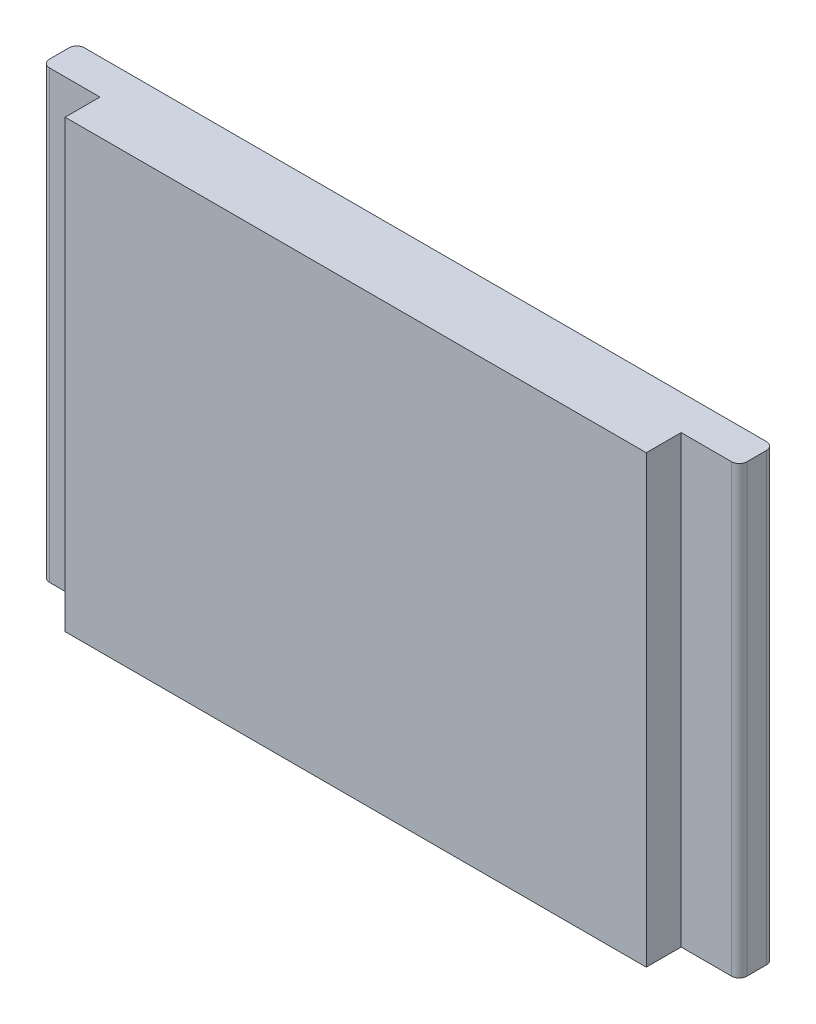
SolidWorks part; units mm, degrees
ref_plane "Front Plane" through (0, 0, 0) normal (0, 0, 1) x (1, 0, 0)
ref_plane "Top Plane" through (0, 0, 0) normal (0, 1, 0) x (1, 0, 0)
ref_plane "Right Plane" through (0, 0, 0) normal (1, 0, 0) x (0, 0, -1)
sketch "Sketch1" plane through (0, 0, 0) normal (0, 1, 0) x (1, 0, 0)
  line L8 (-98.7886, 34.8082) -> (-98.7886, 29.8082)
  line L9 (-96.7886, 27.8082) -> (-83.7886, 27.8082)
  line L10 (-83.7886, 27.8082) -> (-83.7886, 18.8082)
  line L11 (-83.7886, 18.8082) -> (66.2114, 18.8082)
  line L12 (66.2114, 18.8082) -> (66.2114, 27.8082)
  line L13 (66.2114, 27.8082) -> (79.2114, 27.8082)
  line L14 (81.2114, 29.8082) -> (81.2114, 34.8082)
  line L15 (79.2114, 36.8082) -> (-96.7886, 36.8082)
  arc A0 (79.2114, 27.8082) -> (81.2114, 29.8082) centre (79.2114, 29.8082) ccw
  arc A1 (81.2114, 34.8082) -> (79.2114, 36.8082) centre (79.2114, 34.8082) ccw
  arc A2 (-98.7886, 29.8082) -> (-96.7886, 27.8082) centre (-96.7886, 29.8082) ccw
  arc A3 (-98.7886, 34.8082) -> (-96.7886, 36.8082) centre (-96.7886, 34.8082) cw
  point P10 (81.2114, 27.8082)
  point P13 (81.2114, 36.8082)
  point P16 (-98.7886, 27.8082)
  point P19 (-98.7886, 36.8082)
  dimension "D7" = 2
  dimension "D1" = 9
  dimension "D2" = 15
  dimension "D3" = 15
  dimension "D4" = 180
  dimension "D5" = 150
  dimension "D6" = 9
extrude "Boss-Extrude2" add sketch "Sketch1" along normal blind 115
sketch "Sketch2" plane through (0, 0, -36.8082) normal (0, 0, -1) x (-1, 0, 0)
  line L0 (27.4083, 82.886) -> (3.4139, 82.886)
  line L1 (3.4139, 82.886) -> (20.114, 66.1859)
  line L2 (20.114, 66.1859) -> (9.3645, 55.4364)
  line L3 (9.3645, 55.4364) -> (33.071, 31.7298)
  line L4 (27.4083, 82.886) -> (31.0555, 86.5332)
  line L5 (31.0555, 86.5332) -> (27.4083, 92.6758)
  line L6 (27.4083, 92.6758) -> (-18.4691, 94.0195)
  line L7 (-18.4691, 94.0195) -> (7.7805, 66.1859)
  line L8 (7.7805, 66.1859) -> (-3.6177, 55.4364)
  line L9 (-3.6177, 55.4364) -> (33.071, 31.7298)
extrude "Cut-Extrude1" cut sketch "Sketch2" against normal blind 2
